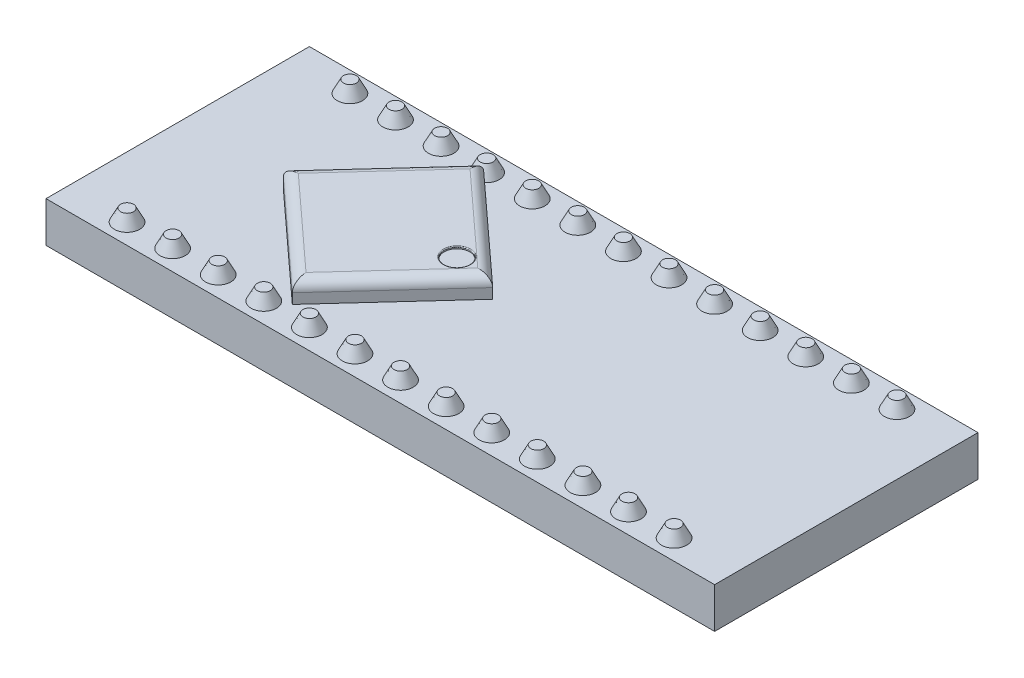
SolidWorks part; units mm, degrees
ref_plane "Front Plane" through (0, 0, 0) normal (0, 0, 1) x (1, 0, 0)
ref_plane "Top Plane" through (0, 0, 0) normal (0, 1, 0) x (1, 0, 0)
ref_plane "Right Plane" through (0, 0, 0) normal (1, 0, 0) x (0, 0, -1)
sketch "Sketch1" plane through (0, 0, 0) normal (0, 1, 0) x (1, 0, 0)
  line L1 (-16.5, 6.5) -> (16.5, 6.5)
  line L2 (-16.5, 6.5) -> (-16.5, -6.5)
  line L3 (-16.5, -6.5) -> (16.5, -6.5)
  line L4 (16.5, 6.5) -> (16.5, -6.5)
  line L5 (-16.5, 6.5) -> (16.5, -6.5) construction
  line L6 (-16.5, -6.5) -> (16.5, 6.5) construction
  point P0 (0, 0)
  dimension "D1" = 13
  dimension "D2" = 33
extrude "Boss-Extrude1" add sketch "Sketch1" along normal blind 2
sketch "Sketch2" plane through (0, 2, 0) normal (0, 1, 0) x (1, 0, 0)
  line L0 (-11.0637, -0.2218) -> (-5.8971, -4.9448)
  line L1 (-11.0637, -0.2218) -> (-6.3407, 4.9448)
  line L2 (-5.8971, -4.9448) -> (-1.1741, 0.2218)
  line L3 (-6.3407, 4.9448) -> (-1.1741, 0.2218)
  line L4 (-11.0637, -0.2218) -> (-1.1741, 0.2218) construction
  line L5 (-5.8971, -4.9448) -> (-6.3407, 4.9448) construction
  point P0 (0, 0)
  point P1 (-6.1189, 0)
  dimension "D1" = 7
  dimension "D2" = 7
extrude "Boss-Extrude2" add sketch "Sketch2" along normal blind 1
fillet "Fillet1" radius 0.5 4 edges at (-3.7574, 3, -2.5833) (-3.5356, 3, 2.3615) (-8.4804, 3, 2.5833) (-8.7022, 3, -2.3615)
sketch "Sketch3" plane through (0, 3, 0) normal (0, 1, 0) x (1, 0, 0)
  circle A0 centre (-2.8689, 0.1515) radius 0.6312
extrude "Cut-Extrude1" cut sketch "Sketch3" against normal blind 0.1
fillet "Fillet2" radius 0.04 1 edges at (-2.8689, 3, 0.4797)
sketch "Sketch4" plane through (0, 2, 0) normal (0, 1, 0) x (1, 0, 0)
  line L0 (16.5, 6.5) -> (-16.5, 6.5) construction
  line L1 (-16.5, 6.5) -> (-16.5, -6.5) construction
  line L3 (-55, 0) -> (55, 0) construction
  circle A0 centre (-13.5, 5.5) radius 0.625
  circle A1 centre (-11.25, 5.5) radius 0.625
  circle A2 centre (-9, 5.5) radius 0.625
  circle A3 centre (-6.75, 5.5) radius 0.625
  circle A4 centre (-4.5, 5.5) radius 0.625
  circle A5 centre (-2.25, 5.5) radius 0.625
  circle A6 centre (0, 5.5) radius 0.625
  circle A7 centre (2.25, 5.5) radius 0.625
  circle A8 centre (4.5, 5.5) radius 0.625
  circle A9 centre (6.75, 5.5) radius 0.625
  circle A10 centre (9, 5.5) radius 0.625
  circle A11 centre (11.25, 5.5) radius 0.625
  circle A12 centre (13.5, 5.5) radius 0.625
  circle A13 centre (-13.5, -5.5) radius 0.625
  circle A14 centre (-11.25, -5.5) radius 0.625
  circle A15 centre (-9, -5.5) radius 0.625
  circle A16 centre (-6.75, -5.5) radius 0.625
  circle A17 centre (-4.5, -5.5) radius 0.625
  circle A18 centre (-2.25, -5.5) radius 0.625
  circle A19 centre (0, -5.5) radius 0.625
  circle A20 centre (2.25, -5.5) radius 0.625
  circle A21 centre (4.5, -5.5) radius 0.625
  circle A22 centre (6.75, -5.5) radius 0.625
  circle A23 centre (9, -5.5) radius 0.625
  circle A24 centre (11.25, -5.5) radius 0.625
  circle A25 centre (13.5, -5.5) radius 0.625
  dimension "D1" = 1
  dimension "D3" = 1.25
  dimension "D2" = 3
  dimension "D4" = 13
  dimension "D5" = 13
extrude "Boss-Extrude3" add sketch "Sketch4" along normal blind 0.6 draft 27 contours A0 | A1 | A2 | A3 | A4 | A5 | A6 | A7 | A8 | A9 | A10 | A11 | A12 | A25 | A24 | A23 | A22 | A21 | A20 | A19 | A18 | A17 | A16 | A15 | A13 | A14
sketch "Sketch6" plane through (0, 3, 0) normal (0, 1, 0) x (1, 0, 0)
  spline S0 degree 1 poles (-7.437, -2.4519) (-7.5994, 1.7699) knots 0 0 1 1
  text T0 "Atmega32" font "Century Gothic" height 0.6
